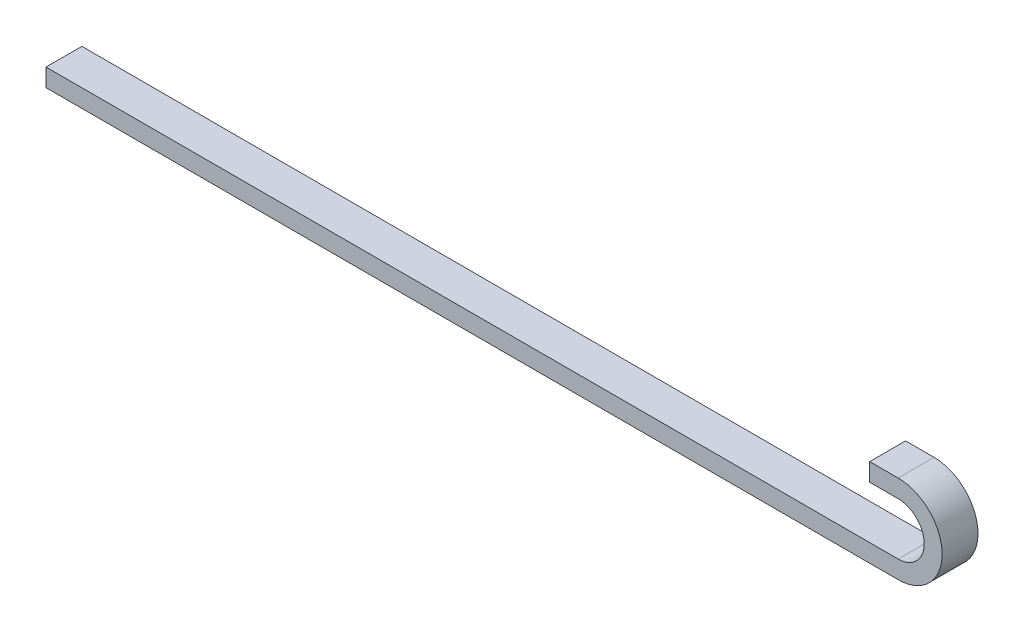
SolidWorks part; units mm, degrees
ref_plane "Front Plane" through (0, 0, 0) normal (0, 0, 1) x (1, 0, 0)
ref_plane "Top Plane" through (0, 0, 0) normal (0, 1, 0) x (1, 0, 0)
ref_plane "Right Plane" through (0, 0, 0) normal (1, 0, 0) x (0, 0, -1)
sketch "Sketch1" plane through (0, 0, 0) normal (0, 0, 1) x (1, 0, 0)
  line L0 (55, 0) -> (-55, 0) construction
  line L1 (-600, 0) -> (0, 0)
  line L2 (-600, 0) -> (-600, 12.6)
  line L3 (-600, 12.6) -> (0, 12.6)
  line L4 (0, -55) -> (0, 55) construction
  line L6 (0, 49.4) -> (-20, 49.4)
  line L8 (0, 62) -> (-20, 62)
  line L9 (-20, 49.4) -> (-20, 62)
  arc A0 (0, 0) -> (0, 62) centre (0, 31) ccw
  arc A1 (0, 12.6) -> (0, 49.4) centre (0, 31) ccw
  dimension "D2" = 31
  dimension "D1" = 62
  dimension "D3" = 12.6
  dimension "D4" = 0
  dimension "D5" = 20
  dimension "D6" = 600
extrude "Boss-Extrude1" add sketch "Sketch1" along normal mid plane 25.25
